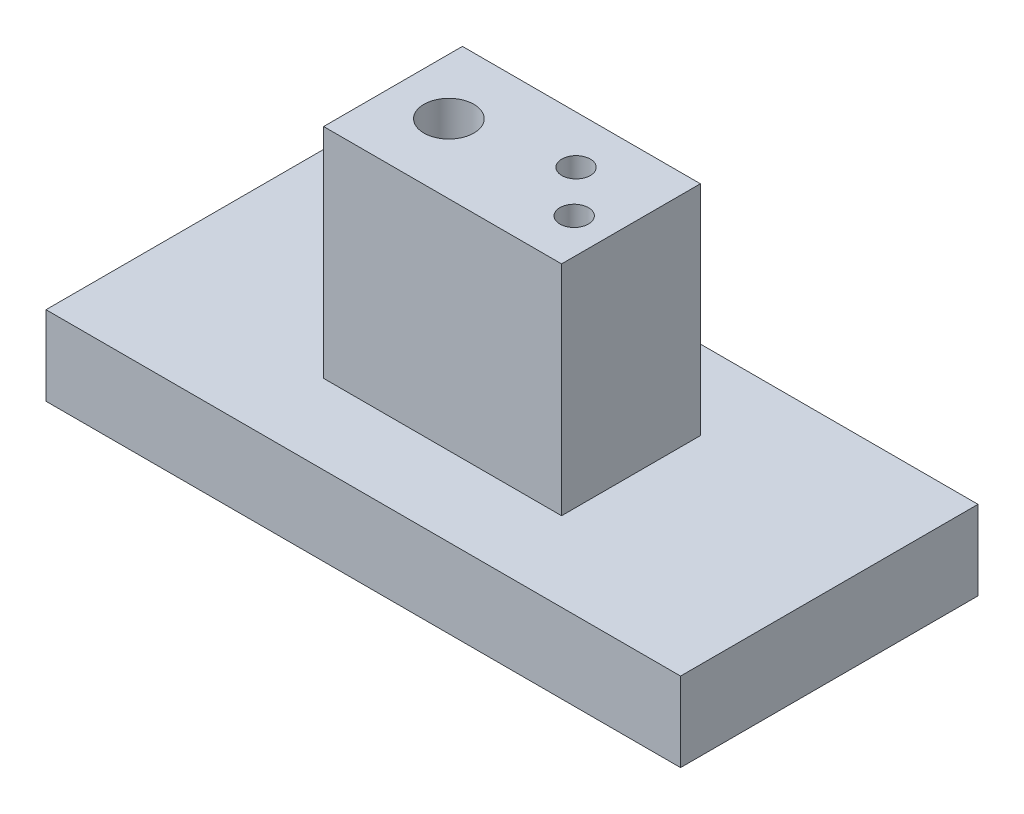
SolidWorks part; units mm, degrees
ref_plane "Front Plane" through (0, 0, 0) normal (0, 0, 1) x (1, 0, 0)
ref_plane "Top Plane" through (0, 0, 0) normal (0, 1, 0) x (1, 0, 0)
ref_plane "Right Plane" through (0, 0, 0) normal (1, 0, 0) x (0, 0, -1)
sketch "Sketch1" plane through (0, 0, 0) normal (0, 1, 0) x (1, 0, 0)
  line L0 (-2.2, 0) -> (2.2, 0) construction
  line L4 (2.1098, -0.542) -> (1.073, 0.542) construction
  line L5 (-1.5914, 0) -> (-0.0707, -1.5898) construction
  line L6 (-0.0707, -1.5898) -> (1.5914, 0) construction
  line L7 (1.5914, 0) -> (2.5308, 0.8986) construction
  line L8 (1.5914, 0) -> (-1.5914, 0) construction
  line L9 (-3, -1.75) -> (3, -1.75)
  line L10 (-3, -1.75) -> (-3, 1.75)
  line L11 (3, -1.75) -> (3, 1.75)
  line L12 (-3, 1.75) -> (3, 1.75)
  line L13 (-3, -1.75) -> (3, 1.75) construction
  line L14 (3, -1.75) -> (-3, 1.75) construction
  circle A0 centre (-2.2, 0) radius 0.63 construction
  circle A1 centre (2.2, 0) radius 0.63 construction
  circle A4 centre (1.073, 0.542) radius 0.36
  circle A5 centre (2.1098, -0.542) radius 0.36
  circle A6 centre (-1.5914, 0) radius 0.63
  point P4 (0, 0)
  point P8 (0, 0)
  point P18 (2.5308, 0.8986)
  point P19 (0, 0)
  dimension "D2" = 1.26
  dimension "D8" = 0.72
  dimension "D1" = 4.4
  dimension "D4" = 1.5
  dimension "D7" = 3.6
  dimension "D6" = 1.3
  dimension "D5" = 2.2
  dimension "D3" = 3.5
  dimension "D9" = 6
extrude "CanulaLayout-Boss-Extrude1" add sketch "Sketch1" along normal blind 5.5
sketch "Sketch2" plane through (0, 0, 0) normal (0, -1, 0) x (1, 0, 0)
  line L0 (-3, 1.75) -> (3, 1.75) construction
  line L1 (-8, 3.75) -> (8, 3.75)
  line L2 (-8, 3.75) -> (-8, -3.75)
  line L3 (-8, -3.75) -> (8, -3.75)
  line L4 (8, 3.75) -> (8, -3.75)
  line L5 (-3, -1.75) -> (-3, 1.75) construction
  line L6 (3, -1.75) -> (-3, -1.75) construction
  line L7 (3, 1.75) -> (3, -1.75) construction
  circle A0 centre (2.1098, 0.542) radius 0.25
  circle A1 centre (1.073, -0.542) radius 0.25
  circle A2 centre (-1.5914, 0) radius 0.25
  dimension "D1" = 0.5
  dimension "D2" = 2
  dimension "D3" = 5
  dimension "D4" = 2
  dimension "D5" = 5
extrude "Base-Boss-Extrude2" add sketch "Sketch2" along normal blind 2
sketch "Sketch3" plane through (0, 0, 0) normal (0, 1, 0) x (1, 0, 0)
  circle A0 centre (-1.5914, 0) radius 0.63
  circle A1 centre (-1.5914, 0) radius 0.25
extrude "HeightDifference-Boss-Extrude3" add sketch "Sketch3" along normal blind 0.2
equation "\"TubingOD\"= 1.26"
equation "\"ConcentricDepth\"= 4.5mm"
equation "\"TubingHeight\"= 5.5mm"
equation "\"D1@CanulaLayout-Boss-Extrude1\" = \"TubingHeight\""
equation "\"D2@Sketch1\"=\"TubingOD\""
equation "\"CanualHeightDifference\"=0.2"
equation "\"D1@HeightDifference-Boss-Extrude3\"=\"CanualHeightDifference\""
